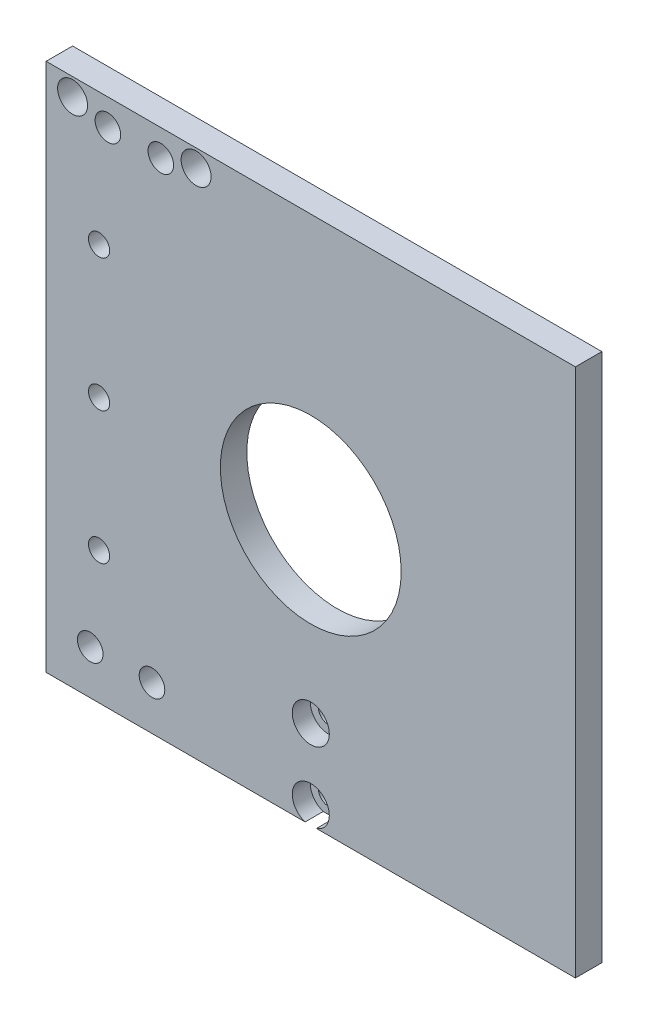
SolidWorks part; units mm, degrees
material "6061-T6 (SS)"
ref_plane "Front Plane" through (0, 0, 0) normal (0, 0, 1) x (1, 0, 0)
ref_plane "Top Plane" through (0, 0, 0) normal (0, 1, 0) x (1, 0, 0)
ref_plane "Right Plane" through (0, 0, 0) normal (1, 0, 0) x (0, 0, -1)
sketch "Sketch1" plane through (0, 0, 0) normal (0, 0, 1) x (1, 0, 0)
  line L1 (30, -30) -> (-30, -30)
  line L2 (30, -30) -> (30, 30)
  line L3 (30, 30) -> (-30, 30)
  line L4 (-30, -30) -> (-30, 30)
  line L5 (30, -30) -> (-30, 30) construction
  line L6 (30, 30) -> (-30, -30) construction
  point P0 (0, 0)
  dimension "D1" = 60
  dimension "D2" = 60
extrude "Boss-Extrude1" add sketch "Sketch1" along normal blind 3
sketch "Sketch2" plane through (0, 0, 3) normal (0, 0, 1) x (1, 0, 0)
  circle A0 centre (0, 0) radius 10.25
extrude "Cut-Extrude1" cut sketch "Sketch2" against normal through all
sketch "Sketch3" plane through (0, 0, 0) normal (0, 0, -1) x (-1, 0, 0)
  circle A0 centre (18, -25) radius 1.45
  circle A1 centre (25, -25) radius 1.45
extrude "Servo_Y_Mount_D2p9" cut sketch "Sketch3" against normal blind 3.01
sketch "Sketch4" plane through (0, 0, 0) normal (0, 0, -1) x (-1, 0, 0)
  circle A0 centre (17, 27) radius 1.45
  circle A1 centre (23, 27) radius 1.45
extrude "Cut-Extrude5" cut sketch "Sketch4" against normal through all
sketch "Sketch5" plane through (0, 0, 3) normal (0, 0, 1) x (1, 0, 0)
  circle A0 centre (-24, -15) radius 1.2
  circle A1 centre (-24, 0) radius 1.2
  circle A2 centre (-24, 15) radius 1.2
extrude "GuideRail1_D2p4" cut sketch "Sketch5" against normal blind 3.01
sketch "Sketch6" plane through (0, 0, 3) normal (0, 0, 1) x (1, 0, 0)
  circle A0 centre (0, -28) radius 1.2
  circle A1 centre (0, -20) radius 1.2
extrude "GuideBlock2_D2p4" cut sketch "Sketch6" against normal blind 3.01
sketch "Sketch7" plane through (0, 0, 3) normal (0, 0, 1) x (1, 0, 0)
  circle A0 centre (0, -28) radius 2.1
  circle A1 centre (0, -20) radius 2.1
extrude "GuideBlock2_HeadCounterbore_D4p2" cut sketch "Sketch7" against normal blind 2.05
sketch "Sketch8" plane through (0, 0, 3) normal (0, 0, 1) x (1, 0, 0)
  circle A0 centre (-27, 28) radius 1.7
  circle A1 centre (-13, 28) radius 1.7
extrude "Bench_XDrop_M3_Clearance_Holes_2x_D3p4" cut sketch "Sketch8" against normal blind 3.5
